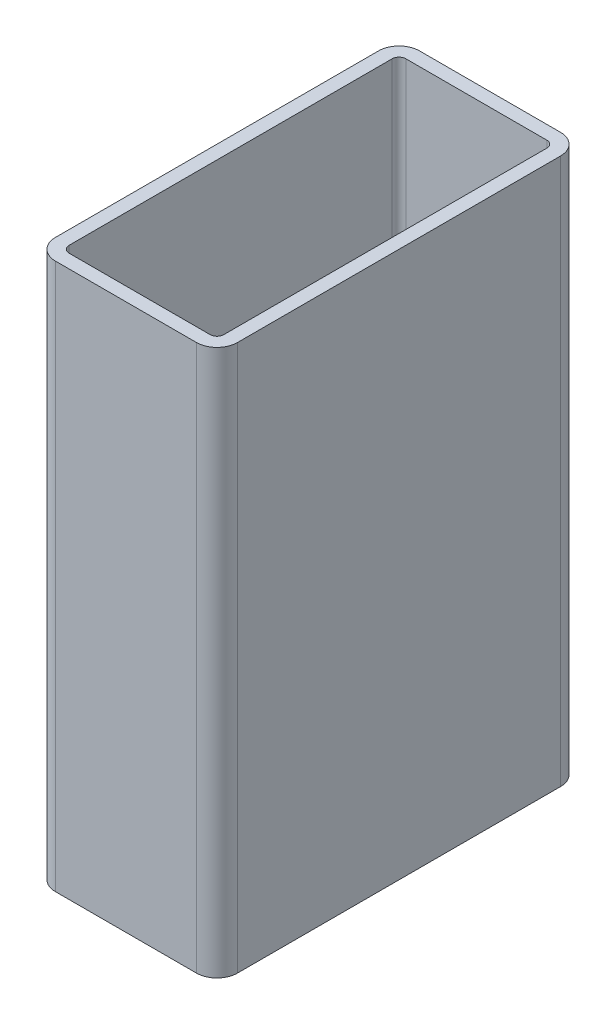
SolidWorks part; units mm, degrees
material "AISI 304"
ref_plane "Спереди" through (0, 0, 0) normal (0, 0, 1) x (1, 0, 0)
ref_plane "Сверху" through (0, 0, 0) normal (0, 1, 0) x (1, 0, 0)
ref_plane "Справа" through (0, 0, 0) normal (1, 0, 0) x (0, 0, -1)
other "Configuration Table"
sketch "Эскиз1" plane through (0, 0, 0) normal (0, 1, 0) x (1, 0, 0)
  line L0 (0, -10) -> (0, 10) construction
  line L1 (-10, -10) -> (-10, 10) construction
  line L2 (10, -10) -> (10, 10) construction
  line L3 (-8.5, -10) -> (-8.5, 10)
  line L4 (8.5, -10) -> (8.5, 10)
  line L5 (-7.75, 18.5) -> (7.75, 18.5)
  line L6 (-7.75, -20) -> (7.75, -20)
  line L7 (-10, -17.75) -> (-10, 17.75)
  line L8 (-7.75, 20) -> (7.75, 20)
  line L9 (10, -17.75) -> (10, 17.75)
  line L10 (-10, -20) -> (10, 20) construction
  line L11 (-10, 20) -> (10, -20) construction
  line L12 (8.5, -17.75) -> (8.5, 17.75)
  line L13 (-7.75, -18.5) -> (7.75, -18.5)
  line L14 (-8.5, -17.75) -> (-8.5, 17.75)
  arc A0 (-10, -10) -> (10, -10) centre (0, -10) ccw construction
  arc A1 (10, 10) -> (-10, 10) centre (0, 10) ccw construction
  arc A2 (8.5, 10) -> (-8.5, 10) centre (0, 10) ccw construction
  arc A3 (-8.5, -10) -> (8.5, -10) centre (0, -10) ccw
  arc A4 (7.75, 20) -> (10, 17.75) centre (7.75, 17.75) cw
  arc A5 (-7.75, -20) -> (-10, -17.75) centre (-7.75, -17.75) cw
  arc A6 (7.75, -20) -> (10, -17.75) centre (7.75, -17.75) ccw
  arc A7 (-10, 17.75) -> (-7.75, 20) centre (-7.75, 17.75) cw
  arc A8 (7.75, 18.5) -> (8.5, 17.75) centre (7.75, 17.75) cw
  arc A9 (7.75, -18.5) -> (8.5, -17.75) centre (7.75, -17.75) ccw
  arc A10 (-7.75, -18.5) -> (-8.5, -17.75) centre (-7.75, -17.75) cw
  arc A11 (-8.5, 17.75) -> (-7.75, 18.5) centre (-7.75, 17.75) cw
  point P2 (0, 0)
  point P8 (10, 0)
  point P15 (0, 0)
  dimension "D1" = 40
  dimension "D4" = 20
  dimension "D6" = 2.25
  dimension "D2" = 20
  dimension "D5" = 40
  dimension "D3" = 1.5
  dimension "D7" = 1.5
extrude "Бобышка-Вытянуть1" add sketch "Эскиз1" along normal mid plane 60 contours L8 A4 L9 A6 L6 A5 L7 A7 | L5 A8 L12 A9 L13 A10 L14 A11
